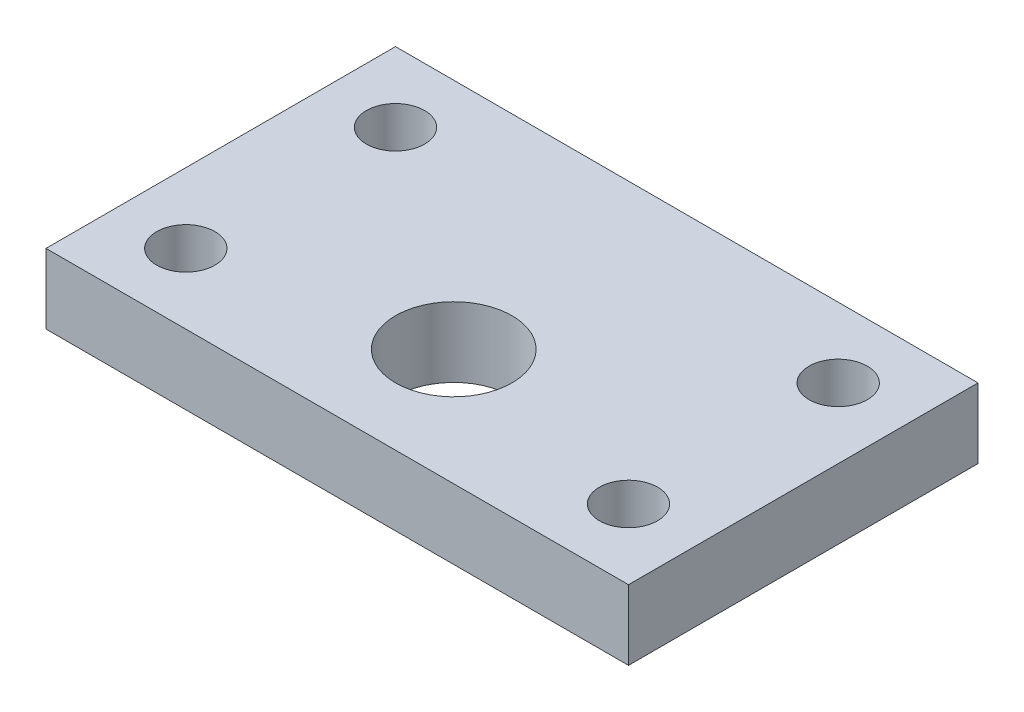
SolidWorks part; units mm, degrees
ref_plane "Front Plane" through (0, 0, 0) normal (0, 0, 1) x (1, 0, 0)
ref_plane "Top Plane" through (0, 0, 0) normal (0, 1, 0) x (1, 0, 0)
ref_plane "Right Plane" through (0, 0, 0) normal (1, 0, 0) x (0, 0, -1)
sketch "Sketch1" plane through (0, 0, 0) normal (0, 1, 0) x (1, 0, 0)
  line L0 (0, 174.8997) -> (0, -149.2139) construction
  line L1 (-125, 75) -> (125, 75)
  line L2 (-125, 75) -> (-125, -75)
  line L3 (-125, -75) -> (125, -75)
  line L4 (125, 75) -> (125, -75)
  line L5 (-125, 75) -> (125, -75) construction
  line L6 (-125, -75) -> (125, 75) construction
  circle A0 centre (0, -25) radius 25
  circle A1 centre (-95, 45) radius 12.5
  circle A2 centre (-95, -45) radius 12.5
  circle A3 centre (95, -45) radius 12.5
  circle A4 centre (95, 45) radius 12.5
  point P0 (0, 0)
  dimension "D5" = 50
  dimension "D6" = 25
  dimension "D1" = 250
  dimension "D2" = 150
  dimension "D3" = 50
  dimension "D4" = 125
  dimension "D7" = 90
  dimension "D8" = 30
  dimension "D9" = 30
  dimension "D10" = 30
extrude "Boss-Extrude1" add sketch "Sketch1" along normal blind 30
